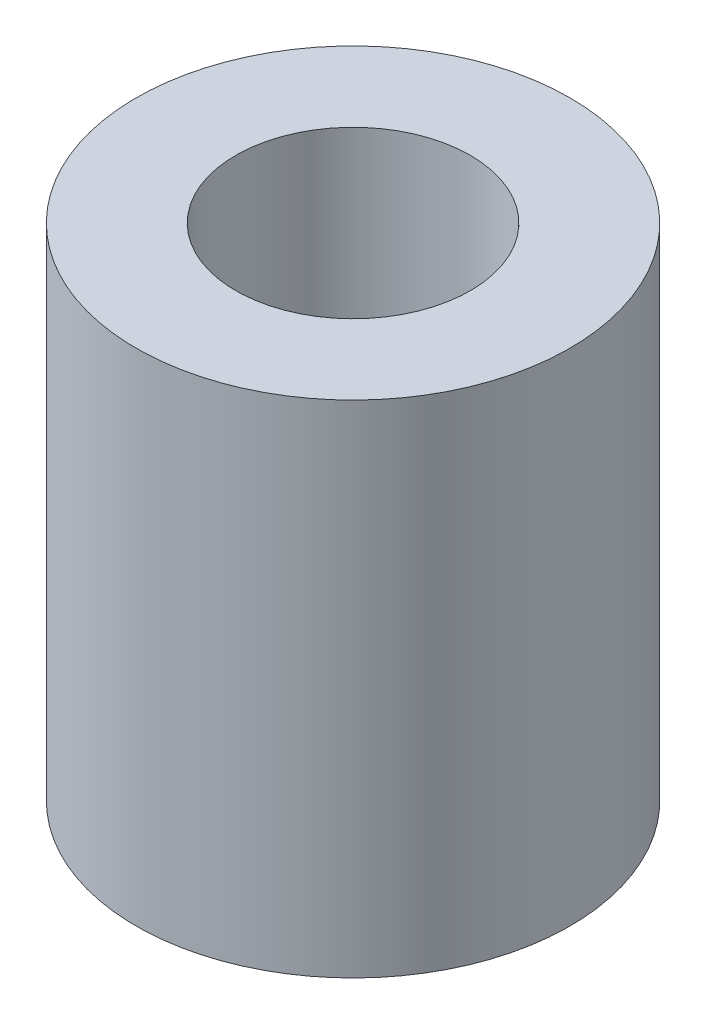
SolidWorks part; units mm, degrees
ref_plane "Front Plane" through (0, 0, 0) normal (0, 0, 1) x (1, 0, 0)
ref_plane "Top Plane" through (0, 0, 0) normal (0, 1, 0) x (1, 0, 0)
ref_plane "Right Plane" through (0, 0, 0) normal (1, 0, 0) x (0, 0, -1)
sketch "Sketch1" plane through (0, 0, 0) normal (1, 0, 0) x (0, 0, -1)
  line L0 (0, 0) -> (0, 38.1) construction
  line L1 (0, 0) -> (-16.51, 0)
  line L2 (-16.51, 0) -> (-16.51, 38.1)
  line L3 (-16.51, 38.1) -> (-8.9281, 38.1)
  line L4 (-8.9281, 38.1) -> (-8.9281, 20.32)
  line L5 (-8.9281, 2.54) -> (0, 2.54)
  line L6 (0, 2.54) -> (0, 0)
  line L7 (-8.9281, 20.32) -> (-10.795, 20.32)
  line L8 (-10.795, 20.32) -> (-10.795, 2.54)
  line L9 (-10.795, 2.54) -> (-8.9281, 2.54)
  dimension "D1" = 38.1
  dimension "D2" = 8.9281
  dimension "D3" = 16.51
  dimension "D4" = 2.54
  dimension "D5" = 21.59
  dimension "D6" = 17.78
revolve "Revolve1" add sketch "Sketch1" angle 360 about L0
sketch "Sketch2" plane through (0, 0, 0) normal (0, -1, 0) x (1, 0, 0)
  circle A0 centre (0, 0) radius 7.366
  dimension "D1" = 14.732
extrude "Cut-Extrude1" cut sketch "Sketch2" against normal up to next
